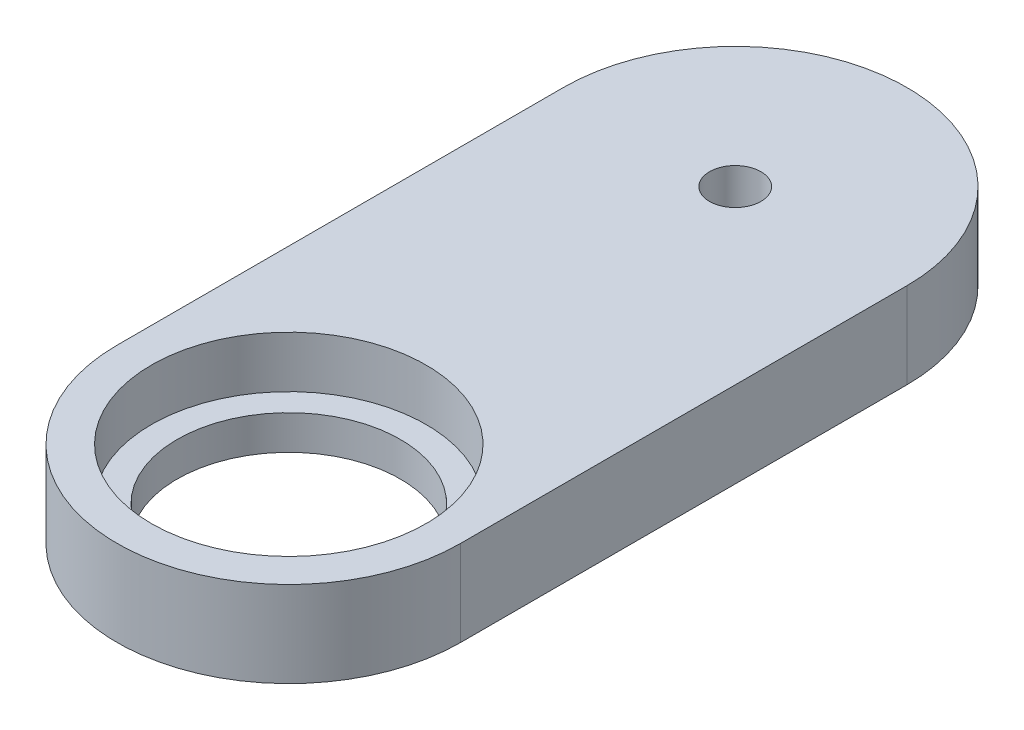
SolidWorks part; units mm, degrees
material "Акрил (Средняя-высокая ударопрочность)"
ref_plane "Спереди" through (0, 0, 0) normal (0, 0, 1) x (1, 0, 0)
ref_plane "Сверху" through (0, 0, 0) normal (0, 1, 0) x (1, 0, 0)
ref_plane "Справа" through (0, 0, 0) normal (1, 0, 0) x (0, 0, -1)
sketch "Эскиз2" plane through (0, 0, 0) normal (0, 1, 0) x (1, 0, 0)
  line L0 (0, 0) -> (0, -26)
  line L1 (0, -26) -> (20, -26) construction
  line L2 (20, -26) -> (20, 0)
  line L3 (20, 0) -> (0, 0) construction
  arc A0 (20, 0) -> (0, 0) centre (10, 0) ccw
  arc A1 (20, -26) -> (0, -26) centre (10, -26) cw
  circle A2 centre (10, 0) radius 1.5
  circle A3 centre (10, -26) radius 6.5
  dimension "D3" = 3
  dimension "D4" = 13
  dimension "D1" = 20
  dimension "D2" = 26
extrude "Бобышка-Вытянуть1" add sketch "Эскиз2" along normal blind 5
sketch "Эскиз3" plane through (0, 5, 0) normal (0, 1, 0) x (1, 0, 0)
  circle A0 centre (10, -26) radius 8
  dimension "D1" = 16
extrude "Вырез-Вытянуть1" cut sketch "Эскиз3" against normal blind 3
